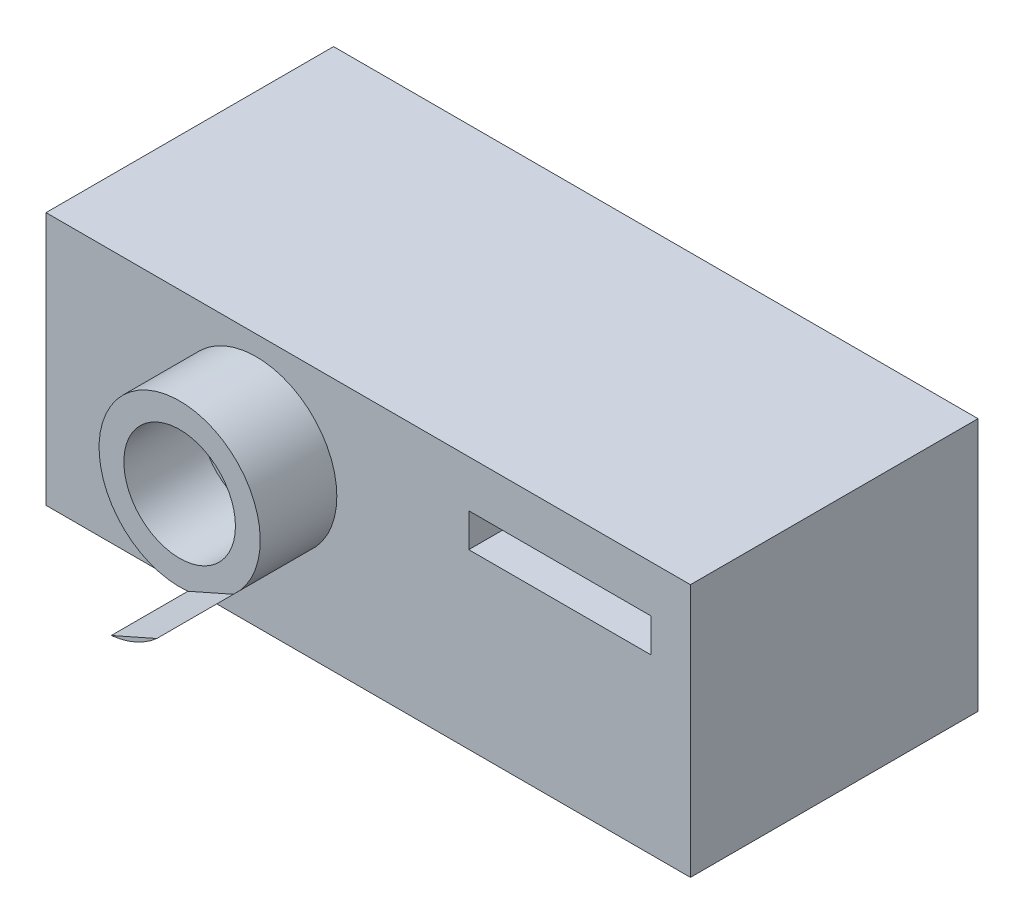
SolidWorks part; units mm, degrees
ref_plane "Front Plane" through (0, 0, 0) normal (0, 0, 1) x (1, 0, 0)
ref_plane "Top Plane" through (0, 0, 0) normal (0, 1, 0) x (1, 0, 0)
ref_plane "Right Plane" through (0, 0, 0) normal (1, 0, 0) x (0, 0, -1)
sketch "Sketch1" plane through (-41.2799, 0, 0) normal (0, 0, 1) x (1, 0, 0)
  line L1 (-37.1176, 17.3524) -> (70.5955, 17.3524)
  line L2 (-37.1176, 17.3524) -> (-37.1176, -25.0239)
  line L3 (-37.1176, -25.0239) -> (70.5955, -25.0239)
  line L4 (70.5955, 17.3524) -> (70.5955, -25.0239)
extrude "Boss-Extrude1" add sketch "Sketch1" along normal blind 47.0645 and the other way blind 1
sketch "Sketch2" plane through (-44.8432, 3.1416, 47.0645) normal (0, 0, 1) x (1, 0, 0)
  circle A0 centre (1.5866, -2.5396) radius 9.3259
  circle A1 centre (1.5866, -2.5396) radius 13.4695
extrude "Boss-Extrude2" add sketch "Sketch2" along normal blind 25.6046
sketch "Sketch3" plane through (0, 0, 72.6691) normal (0, 0, 1) x (1, 0, 0)
  line L1 (-21.6472, -17.0486) -> (-21.0301, -14.4309)
  line L2 (-21.0301, -14.4309) -> (-22.0696, -11.9505)
  line L3 (-22.0696, -11.9505) -> (-24.3684, -10.5547)
  line L4 (-24.3684, -10.5547) -> (-27.0487, -10.7768)
  line L5 (-27.0487, -10.7768) -> (-29.0865, -12.5318)
  line L6 (-29.0865, -12.5318) -> (-29.7036, -15.1495)
  line L7 (-29.7036, -15.1495) -> (-28.6642, -17.6299)
  line L8 (-28.6642, -17.6299) -> (-26.3653, -19.0257)
  line L9 (-26.3653, -19.0257) -> (-23.685, -18.8037)
  line L10 (-23.685, -18.8037) -> (-21.6472, -17.0486)
  line L11 (-18.4929, -30.3388) -> (-15.3384, -1.0629)
  line L12 (-15.3384, -1.0629) -> (-42.2693, -12.9689)
  line L13 (-42.2693, -12.9689) -> (-18.4929, -30.3388)
  circle A0 centre (-25.3669, -14.7902) radius 4.1386 construction
  circle A1 centre (-25.3669, -14.7902) radius 8.5001 construction
extrude "Cut-Extrude2" cut sketch "Sketch3" against normal mid plane 25.6046 flip side to cut contours L12 L13 L11
sketch "Sketch5" plane through (0, 0, 47.0645) normal (0, 0, 1) x (1, 0, 0)
  line L1 (-7.7326, 3.894) -> (22.6942, 3.894)
  line L2 (-7.7326, 3.894) -> (-7.7326, 9.5274)
  line L3 (-7.7326, 9.5274) -> (22.6942, 9.5274)
  line L4 (22.6942, 3.894) -> (22.6942, 9.5274)
extrude "Cut-Extrude3" cut sketch "Sketch5" against normal blind 19.6046
sketch "Sketch6" plane through (0, 0, 72.6691) normal (0, 0, 1) x (1, 0, 0)
